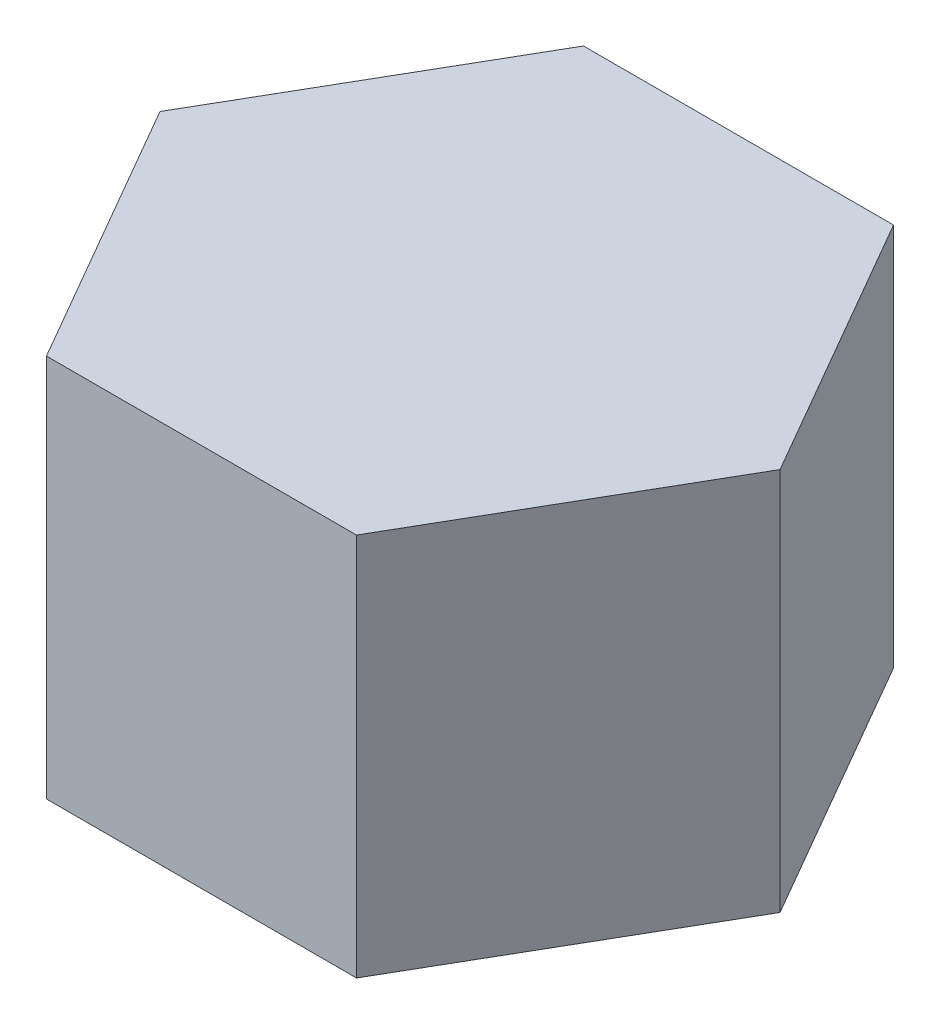
SolidWorks part; units mm, degrees
ref_plane "前视基准面" through (0, 0, 0) normal (0, 0, 1) x (1, 0, 0)
ref_plane "上视基准面" through (0, 0, 0) normal (0, 1, 0) x (1, 0, 0)
ref_plane "右视基准面" through (0, 0, 0) normal (1, 0, 0) x (0, 0, -1)
sketch "草图1" plane through (0, 0, 0) normal (0, 1, 0) x (1, 0, 0)
  line L1 (88.9119, 0) -> (44.456, 77)
  line L2 (44.456, 77) -> (-44.456, 77)
  line L3 (-44.456, 77) -> (-88.9119, 0)
  line L4 (-88.9119, 0) -> (-44.456, -77)
  line L5 (-44.456, -77) -> (44.456, -77)
  line L6 (44.456, -77) -> (88.9119, 0)
  circle A0 centre (0, 0) radius 77 construction
  dimension "D1" = 77
extrude "凸台-拉伸1" add sketch "草图1" along normal blind 80 and the other way blind 30
